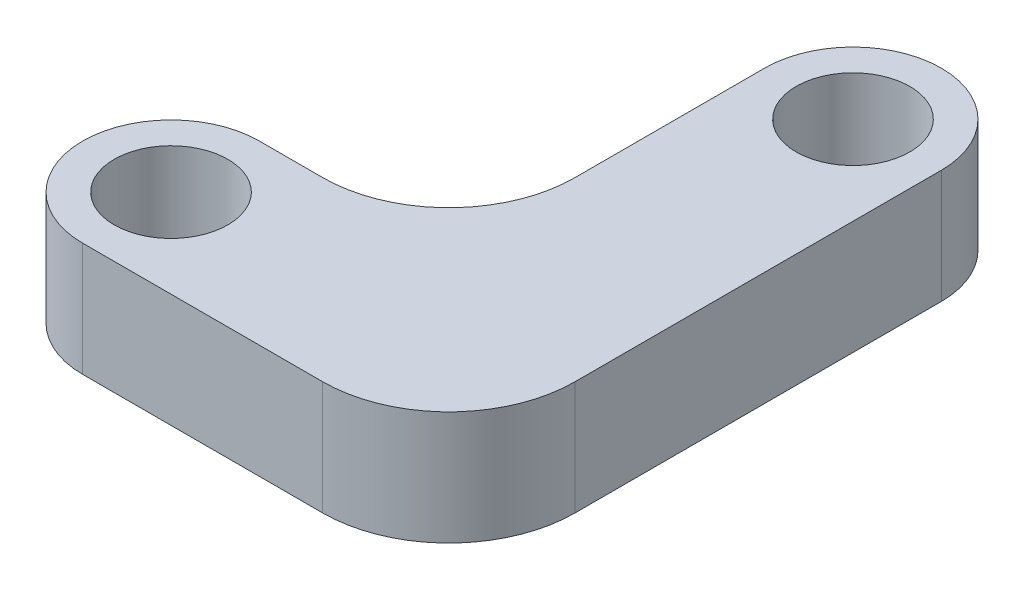
SolidWorks part; units mm, degrees
ref_plane "前视基准面" through (0, 0, 0) normal (0, 0, 1) x (1, 0, 0)
ref_plane "上视基准面" through (0, 0, 0) normal (0, 1, 0) x (1, 0, 0)
ref_plane "右视基准面" through (0, 0, 0) normal (1, 0, 0) x (0, 0, -1)
sketch "草图1" plane through (0, 0, 0) normal (0, 0, 1) x (1, 0, 0)
  line L0 (0, 0) -> (7, 0)
  line L1 (0, 0) -> (-7, 0)
  line L2 (7, 0) -> (7, -9)
  line L3 (7, -9) -> (-7, -9)
  line L4 (-7, -9) -> (-7, 0)
  dimension "D1" = 7
  dimension "D2" = 7
  dimension "D3" = 9
extrude "凸台-拉伸1" add sketch "草图1" along normal blind 25
sketch "草图2" plane through (0, 0, 0) normal (0, 1, 0) x (1, 0, 0)
  line L0 (7, 0) -> (-7, 0) construction
  line L1 (7, 0) -> (-7, 0)
  arc A0 (7, 0) -> (-7, 0) centre (0, 0) ccw
extrude "凸台-拉伸2" add sketch "草图2" against normal blind 9
sketch "草图3" plane through (0, 0, 0) normal (0, 1, 0) x (1, 0, 0)
  circle A0 centre (0, 0) radius 4.5
  dimension "D1" = 9
extrude "切除-拉伸1" cut sketch "草图3" against normal blind 9
sketch "草图5" plane through (-7, 0, 0) normal (-1, 0, 0) x (0, 0, 1)
  line L0 (25, 0) -> (39, 0)
  line L1 (25, 0) -> (25, -9)
  line L2 (25, -9) -> (39, -9)
  line L3 (39, -9) -> (39, 0)
  dimension "D1" = 14
extrude "凸台-拉伸3" add sketch "草图5" along normal blind 15 separate body
sketch "草图6" plane through (0, 0, 0) normal (0, 1, 0) x (1, 0, 0)
  line L0 (-22, -25) -> (-22, -39)
  arc A0 (-22, -25) -> (-22, -39) centre (-22, -32) ccw
extrude "凸台-拉伸4" add sketch "草图6" against normal blind 9
sketch "草图7" plane through (0, 0, 0) normal (0, 1, 0) x (1, 0, 0)
  circle A0 centre (-22, -32) radius 4.5
  dimension "D1" = 9
extrude "切除-拉伸2" cut sketch "草图7" against normal blind 9
sketch "草图8" plane through (0, 0, 0) normal (0, 1, 0) x (1, 0, 0)
  line L0 (7, -25) -> (-7, -25) construction
  line L1 (7, -25) -> (-7, -25)
  line L2 (-7, -39) -> (-7, -25) construction
  line L3 (-7, -39) -> (-7, -25)
  line L4 (7, -25) -> (7, -39)
  line L5 (7, -39) -> (-7, -39)
extrude "凸台-拉伸5" add sketch "草图8" against normal blind 9
fillet "圆角1" radius 10 2 edges at (7, -4.5, 39) (-7, -4.5, 25)
